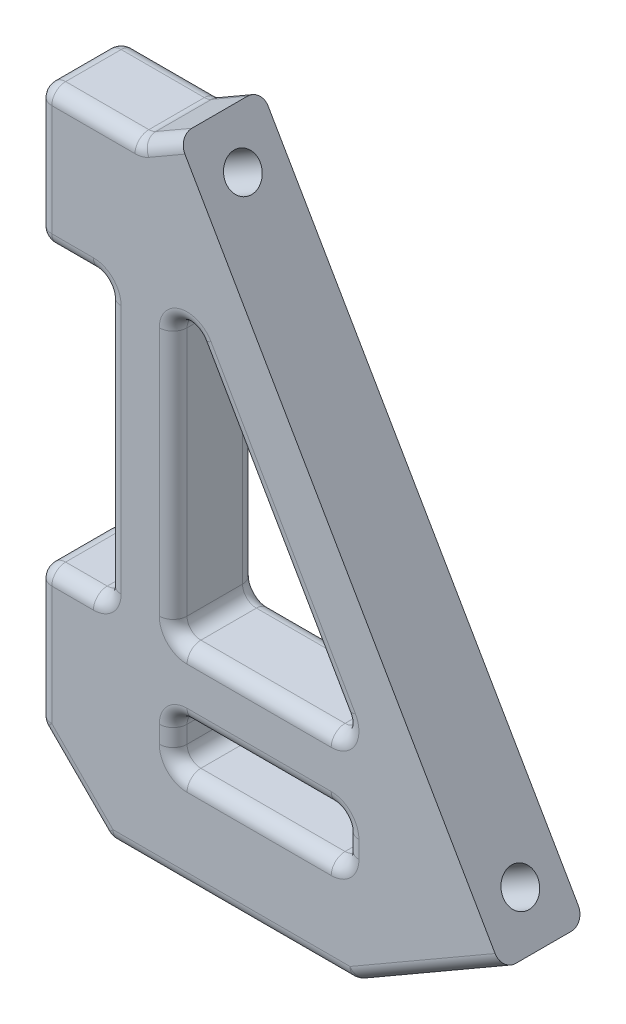
SolidWorks part; units mm, degrees
ref_plane "Спереди" through (0, 0, 0) normal (0, 0, 1) x (1, 0, 0)
ref_plane "Сверху" through (0, 0, 0) normal (0, 1, 0) x (1, 0, 0)
ref_plane "Справа" through (0, 0, 0) normal (1, 0, 0) x (0, 0, -1)
sketch "Эскиз1" plane through (0, 0, 0) normal (0, 0, 1) x (1, 0, 0)
  line L0 (5, 0) -> (0, 5)
  line L1 (0, 5) -> (0, 15)
  line L2 (0, 15) -> (5, 15)
  line L3 (5, 15) -> (5, 35)
  line L4 (5, 35) -> (0, 35)
  line L5 (0, 35) -> (0, 45)
  line L6 (0, 45) -> (7, 45)
  line L7 (7.5, 45.134) -> (10.0981, 46.634)
  line L8 (10.0981, 46.634) -> (33.4586, 6.1723)
  line L9 (33.4586, 6.1723) -> (23, 0.134)
  line L10 (22.5, 0) -> (5, 0)
  arc A0 (22.5, 0) -> (23, 0.134) centre (22.5, 1) ccw
  arc A1 (7, 45) -> (7.5, 45.134) centre (7, 46) ccw
  dimension "D1" = 1
  dimension "D2" = 45
  dimension "D3" = 5
  dimension "D4" = 45
  dimension "D5" = 10
  dimension "D6" = 10
  dimension "D7" = 5
  dimension "D8" = 7
  dimension "D9" = 22.5
  dimension "D10" = 60
  dimension "D11" = 3
extrude "Бобышка-Вытянуть1" add sketch "Эскиз1" along normal blind 6
sketch "Эскиз2" plane through (0, 0, 6) normal (0, 0, 1) x (1, 0, 0)
  line L0 (9.7513, 34) -> (9.7513, 15)
  line L1 (9.7513, 15) -> (21.1436, 15)
  line L2 (22.0096, 16.5) -> (11.6173, 34.5)
  line L3 (33.4586, 6.1723) -> (10.0981, 46.634) construction
  line L4 (5, 15) -> (0, 15) construction
  line L7 (5, 19.0469) -> (9.7513, 19.0469) construction
  line L8 (5, 35) -> (5, 15) construction
  line L9 (19.9109, 20.135) -> (24.0257, 22.5107) construction
  line L10 (-6.9378, 40) -> (7.153, 40) construction
  line L11 (21.0956, 47.2099) -> (9.5959, 40.5705) construction
  line L12 (10.0981, 46.634) -> (7.5, 45.134) construction
  line L13 (13.75, 7.7656) -> (13.75, -5.1092) construction
  line L15 (42.9352, 17.4171) -> (26.7877, 8.0943) construction
  line L16 (23, 0.134) -> (33.4586, 6.1723) construction
  line L17 (5, 0) -> (22.5, 0) construction
  line L18 (-5.9364, 10) -> (6.3662, 10) construction
  line L19 (19.6886, 10.2487) -> (19.6886, 15) construction
  line L20 (9.7513, 10.2487) -> (22.1436, 10.2487)
  line L21 (9.7513, 10.2487) -> (9.7513, 7)
  line L22 (9.7513, 7) -> (22.1436, 7)
  line L24 (22.1436, 10.2487) -> (22.1436, 7)
  line L26 (0, 35) -> (5, 35) construction
  arc A0 (11.6173, 34.5) -> (9.7513, 34) centre (10.7513, 34) ccw
  arc A1 (21.1436, 15) -> (22.0096, 16.5) centre (21.1436, 16) ccw
  point P23 (13.75, 0)
  dimension "D3" = 5
  dimension "D4" = 1
  dimension "D1" = 5
  dimension "D2" = 7
extrude "Вырез-Вытянуть1" cut sketch "Эскиз2" against normal blind 6
sketch "Эскиз3" plane through (0, 0, 0) normal (-1, 0, 0) x (0, 0, 1)
  line L0 (6, 15) -> (6, 5) construction
  line L1 (6, 5) -> (0, 5) construction
  line L2 (6, 45) -> (6, 35) construction
  line L3 (6, 35) -> (0, 35) construction
  circle A0 centre (3, 40) radius 1.25
  circle A1 centre (3, 10) radius 1.25
  point P4 (6, 10)
  point P5 (3, 5)
  point P8 (6, 40)
  point P11 (3, 35)
  dimension "D1" = 2.5
extrude "Вырез-Вытянуть2" cut sketch "Эскиз3" against normal blind 6
sketch "Эскиз4" plane through (0, 0, 0) normal (0, -1, 0) x (1, 0, 0)
  line L0 (0, 6) -> (0, 0) construction
  line L1 (5, 0) -> (22.5, 0) construction
  circle A0 centre (13.75, 3) radius 1.25
  point P0 (0, 3)
  point P1 (13.75, 0)
  dimension "D1" = 2.5
extrude "Вырез-Вытянуть3" cut sketch "Эскиз4" against normal blind 6
sketch "Эскиз5" plane through (27.7667, 16.0311, 0) normal (0.866, 0.5, 0) x (0, 0, -1)
  line L0 (-6, 35.3372) -> (0, 35.3372) construction
  line L1 (-6, -11.384) -> (0, -11.384) construction
  line L2 (-3, 31.9766) -> (-3, 35.3372) construction
  line L3 (-3, -8.0234) -> (-3, -11.384) construction
  circle A0 centre (-3, 31.9766) radius 1.25
  circle A1 centre (-3, -8.0234) radius 1.25
  point P0 (-3, 35.3372)
  point P1 (-3, -11.384)
  dimension "D2" = 2.5
  dimension "D1" = 40
extrude "Вырез-Вытянуть4" cut sketch "Эскиз5" against normal blind 6
fillet "Скругление1" radius 1 12 edges at (22.1436, 7, 3) (22.1436, 10.2487, 3) (9.7513, 7, 3) (9.7513, 10.2487, 3) (9.7513, 15, 3) (5, 0, 3) (0, 5, 3) (0, 15, 3) (5, 15, 3) (0, 45, 3) (5, 35, 3) (0, 35, 3)
fillet "Скругление2" radius 1 66 edges at (10.0442, 9.9558, 6) (15.9474, 10.2487, 6) (21.8507, 9.9558, 6) (22.1436, 8.6244, 6) (21.8507, 7.2929, 6) (15.9474, 7, 6) (10.0442, 7.2929, 6) (10.4925, 34.9659, 6) (16.8135, 25.5, 6) (22.0096, 15.5, 6) (15.9474, 15, 6) (10.0442, 15.2929, 6) (8.799, 45.884, 6) (7.2588, 45.0341, 6) (4, 45, 6) (0.2929, 44.7071, 6) (0, 40, 6) (0.2929, 35.2929, 6) (2.5, 35, 6) (4.7071, 34.7071, 6) (28.2293, 3.1531, 6) (22.7588, 0.0341, 6) (13.9571, 0, 6) (5.0315, 0.0761, 6) (2.5, 2.5, 6) (0.0761, 5.0315, 6) (0, 9.7071, 6) (0.2929, 14.7071, 6) (2.5, 15, 6) (4.7071, 15.2929, 6) (8.799, 45.884, 0) (7.2588, 45.0341, 0) (4, 45, 0) (0.2929, 44.7071, 0) (0, 40, 0) (0.2929, 35.2929, 0) (2.5, 35, 0) (4.7071, 34.7071, 0) (28.2293, 3.1531, 0) (22.7588, 0.0341, 0) (13.9571, 0, 0) (5.0315, 0.0761, 0) (2.5, 2.5, 0) (0.0761, 5.0315, 0) (0, 9.7071, 0) (0.2929, 14.7071, 0) (2.5, 15, 0) (4.7071, 15.2929, 0) (21.8507, 9.9558, 0) (22.1436, 8.6244, 0) (21.8507, 7.2929, 0) (15.9474, 7, 0) (10.0442, 7.2929, 0) (9.7513, 8.6244, 0) (10.0442, 9.9558, 0) (22.0096, 15.5, 0) (15.9474, 15, 0) (10.0442, 15.2929, 0) (9.7513, 25, 0) (10.4925, 34.9659, 0) (9.7513, 8.6244, 6) (9.7513, 25, 6) (5, 25, 6) (5, 25, 0) (15.9474, 10.2487, 0) (16.8135, 25.5, 0)
equation "\"Радиус скругления\"= 1"
equation "\"D1@Эскиз1\"=\"Радиус скругления\""
equation "\"D1@Скругление1\"=\"Радиус скругления\""
equation "\"D4@Эскиз2\"=\"Радиус скругления\""
equation "\"D1@Скругление2\"=\"Радиус скругления\""
